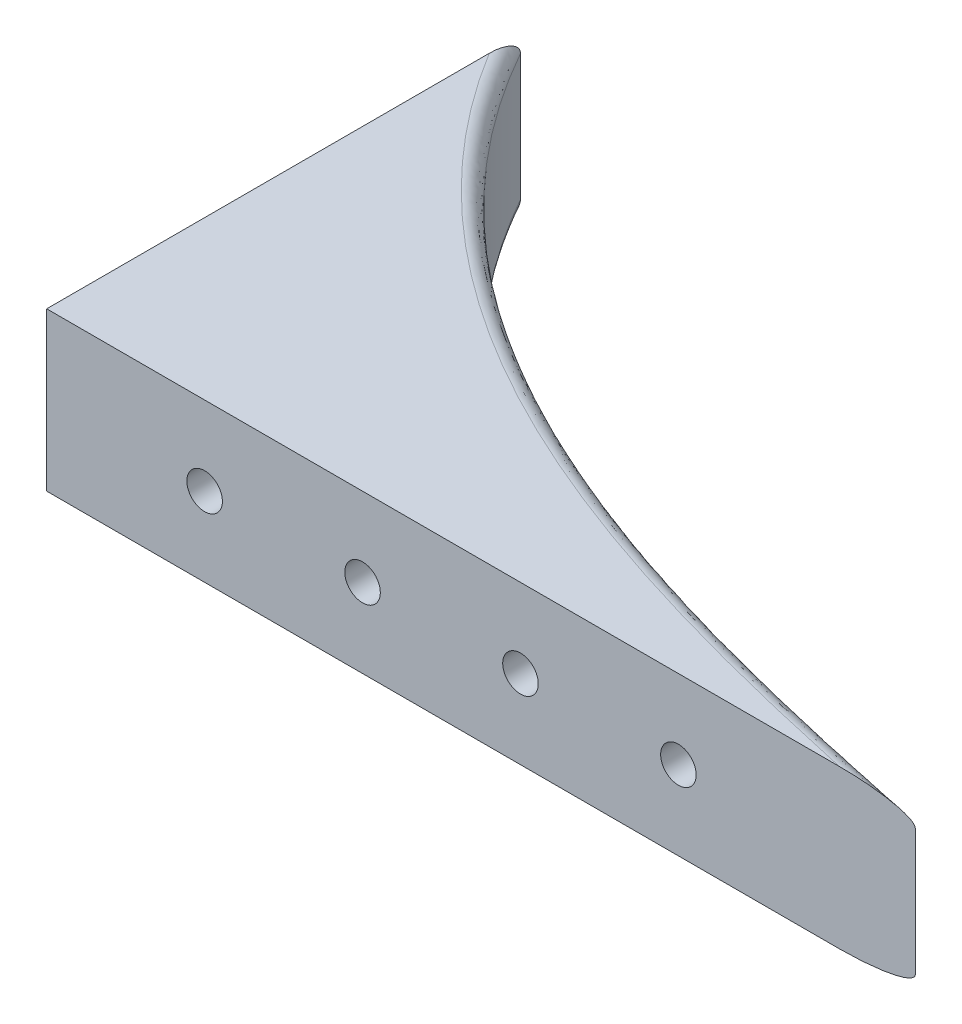
SolidWorks part; units mm, degrees
ref_plane "Front Plane" through (0, 0, 0) normal (0, 0, 1) x (1, 0, 0)
ref_plane "Top Plane" through (0, 0, 0) normal (0, 1, 0) x (1, 0, 0)
ref_plane "Right Plane" through (0, 0, 0) normal (1, 0, 0) x (0, 0, -1)
sketch "Sketch2" plane through (0, 0, 0) normal (0, 1, 0) x (1, 0, 0)
  line L0 (-31.3653, 0) -> (78.6347, 0)
  line L1 (-31.3653, 0) -> (-31.3653, 60)
  spline S0 degree 3 poles (-31.3653, 60) (-8.4219, 19.0526) (40.3763, 8.009) (78.6347, 0) knots 0 0 0 0 1 1 1 1
  dimension "D1" = 110
  dimension "D2" = 60
extrude "Boss-Extrude1" add sketch "Sketch2" along normal blind 20
sketch "Sketch3" plane through (0, 0, 0) normal (0, 0, 1) x (1, 0, 0)
  line L0 (-31.3653, 20) -> (-31.3653, 0) construction
  line L1 (-31.3653, 10) -> (78.6347, 10) construction
  line L2 (78.6347, 20) -> (78.6347, 0) construction
  circle A0 centre (-11.3653, 10) radius 2.5
  circle A1 centre (8.6347, 10) radius 2.5
  circle A2 centre (28.6347, 10) radius 2.5
  circle A3 centre (48.6347, 10) radius 2.5
  dimension "D1" = 5
  dimension "D2" = 20
  dimension "D3" = 4
extrude "Cut-Extrude1" cut sketch "Sketch3" against normal through all
sketch "Sketch4" plane through (0, 0, 0) normal (0, 0, 1) x (1, 0, 0)
  circle A1 centre (-11.3653, 10) radius 2.5
  circle A2 centre (8.6347, 10) radius 2.5
  circle A3 centre (28.6347, 10) radius 2.5
  circle A4 centre (48.6347, 10) radius 2.5
  dimension "D1" = 5
  dimension "D2" = 4
extrude "Boss-Extrude2" add sketch "Sketch4" against normal blind 5
sketch "Sketch5" plane through (0, 0, 0) normal (0, 0, 1) x (1, 0, 0)
  line L0 (-11.3653, 10) -> (8.6347, 10) construction
  circle A0 centre (-11.3653, 10) radius 2.25
  circle A1 centre (8.6347, 10) radius 2.25
  circle A2 centre (28.6347, 10) radius 2.25
  circle A3 centre (48.6347, 10) radius 2.25
  dimension "D1" = 4.5
  dimension "D3" = 20
  dimension "D2" = 4
extrude "Cut-Extrude2" cut sketch "Sketch5" against normal through all
fillet "Fillet2" radius 2 2 edges
